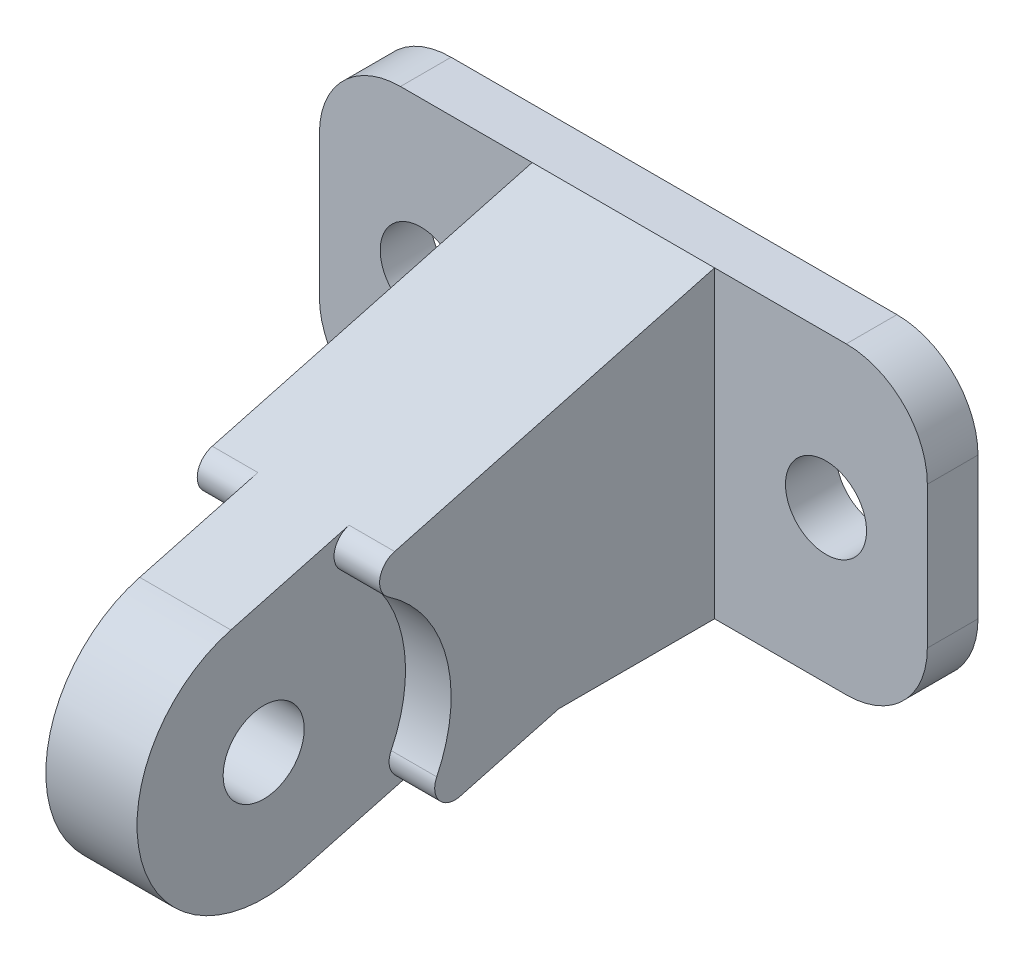
SolidWorks part; units mm, degrees
ref_plane "Front Plane" through (0, 0, 0) normal (0, 0, 1) x (1, 0, 0)
ref_plane "Top Plane" through (0, 0, 0) normal (0, 1, 0) x (1, 0, 0)
ref_plane "Right Plane" through (0, 0, 0) normal (1, 0, 0) x (0, 0, -1)
other "Configuration Table"
sketch "Sketch1" plane through (0, 0, 0) normal (0, 0, 1) x (1, 0, 0)
  line L1 (-30, 15) -> (30, 15)
  line L2 (-30, 15) -> (-30, -15)
  line L3 (-30, -15) -> (30, -15)
  line L4 (30, 15) -> (30, -15)
  line L5 (0, -15) -> (0, 15) construction
  line L6 (-30, 0) -> (30, 0) construction
  circle A0 centre (-20, 0) radius 4
  circle A1 centre (20, 0) radius 4
  point P0 (0, 0)
  dimension "D1" = 8
  dimension "D2" = 60
  dimension "D3" = 30
  dimension "D4" = 40
extrude "Boss-Extrude1" add sketch "Sketch1" along normal mid plane 5
fillet "Fillet1" radius 8 4 edges at (30, -15, 0) (-30, -15, 0) (30, 15, 0) (-30, 15, 0)
sketch "Sketch3" plane through (0, 0, 0) normal (1, 0, 0) x (0, 0, -1)
  line L0 (-2.5, 15) -> (-45.7352, 3.4152)
  line L1 (-39.2648, -20.733) -> (-17.8689, -15)
  line L2 (-17.8689, -15) -> (-2.5, -15)
  line L3 (-2.5, -15) -> (-2.5, 15)
  arc A0 (-45.7352, 3.4152) -> (-39.2648, -20.733) centre (-42.5, -8.6589) ccw
  circle A1 centre (-42.5, -8.6589) radius 4
  dimension "D1" = 12.5
  dimension "D4" = 8
  dimension "D2" = 40
  dimension "D3" = 15
extrude "Boss-Extrude2" add sketch "Sketch3" along normal mid plane 18
sketch "Sketch4" plane through (9, 0, 0) normal (1, 0, 0) x (0, 0, -1)
  circle A0 centre (-42.5, -8.6589) radius 14
  dimension "D1" = 28
extrude "Cut-Extrude1" cut sketch "Sketch4" against normal blind 4.5
fillet "Fillet2" radius 2 2 edges at (6.75, -19.1012, 33.1748) (6.75, 5.0469, 39.6453)
mirror "Mirror1" about plane through (0, 0, 0) normal (1, 0, 0) of "Cut-Extrude1", "Fillet2"
equation "\"GAUGE\"= SWITCH ( \"Thickness\" < 0.9 , 0 , \"Thickness\" < 1.1 , 20 , \"Thickness\" < 1.6 , 16 , \"Thickness\" < 2.1 , 14 , \"Thickness\" < 3.1 , 11 , \"Thickness\" < 4.8 , 7 , \"Thickness\" > 4.8 , 0 )"
